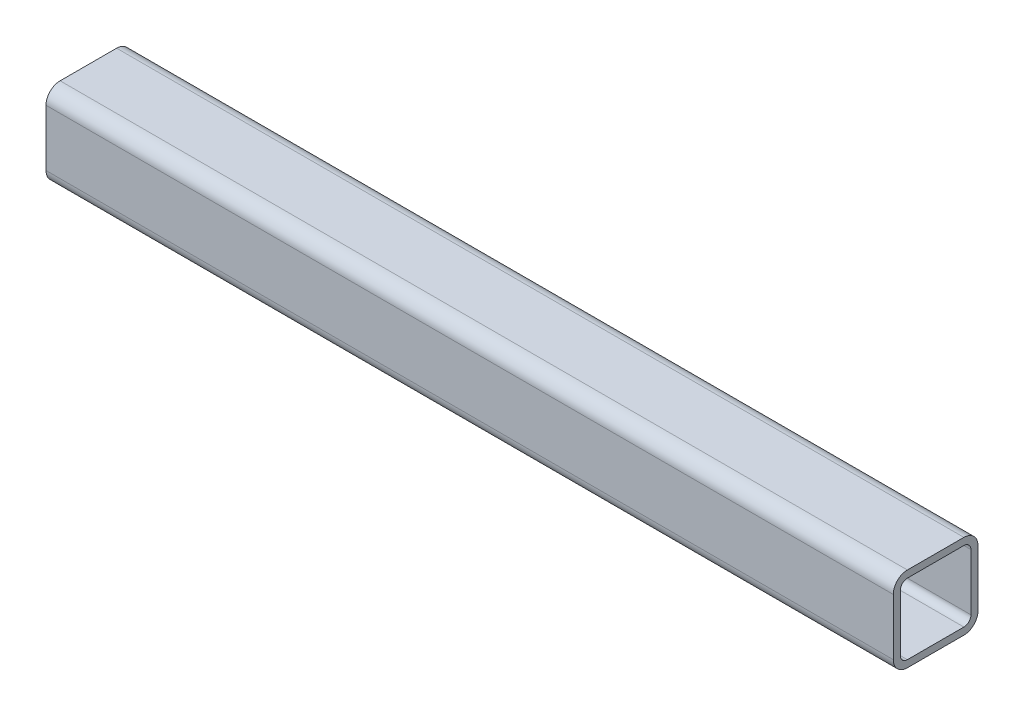
SolidWorks part; units mm, degrees
material "Plain Carbon Steel"
ref_plane "Front Plane" through (0, 0, 0) normal (0, 0, 1) x (1, 0, 0)
ref_plane "Top Plane" through (0, 0, 0) normal (0, 1, 0) x (1, 0, 0)
ref_plane "Right Plane" through (0, 0, 0) normal (1, 0, 0) x (0, 0, -1)
sketch3d "3DSketch1"
  line L0 (0, 0, 0) -> (-762, 0, 0)
  dimension "D1" = 762
other "Structural Member1"
ref_plane "Plane1" through (0, 0, 0) normal (-1, 0, 0) x (0, 0, 1)
sketch "Sketch1" plane through (0, 0, 0) normal (-1, 0, 0) x (0, 0, 1)
  line L0 (-25.4, -31.75) -> (25.4, -31.75)
  line L1 (-31.75, -25.4) -> (-31.75, 25.4)
  line L2 (25.4, 31.75) -> (-25.4, 31.75)
  line L3 (31.75, 25.4) -> (31.75, -25.4)
  line L4 (-25.4, -38.1) -> (25.4, -38.1)
  line L5 (-38.1, -25.4) -> (-38.1, 25.4)
  line L6 (25.4, 38.1) -> (-25.4, 38.1)
  line L7 (38.1, 25.4) -> (38.1, -25.4)
  line L8 (0, 0) -> (31.75, 0) construction
  line L9 (0, 0) -> (0, 31.75) construction
  arc A0 (38.1, 25.4) -> (25.4, 38.1) centre (25.4, 25.4) ccw
  arc A1 (25.4, -38.1) -> (38.1, -25.4) centre (25.4, -25.4) ccw
  arc A2 (-38.1, -25.4) -> (-25.4, -38.1) centre (-25.4, -25.4) ccw
  arc A3 (-25.4, 38.1) -> (-38.1, 25.4) centre (-25.4, 25.4) ccw
  arc A4 (-25.4, 31.75) -> (-31.75, 25.4) centre (-25.4, 25.4) ccw
  arc A5 (31.75, 25.4) -> (25.4, 31.75) centre (25.4, 25.4) ccw
  arc A6 (25.4, -31.75) -> (31.75, -25.4) centre (25.4, -25.4) ccw
  arc A7 (-31.75, -25.4) -> (-25.4, -31.75) centre (-25.4, -25.4) ccw
  point P3 (0, 38.1)
  point P4 (38.1, 0)
  point P5 (0, -38.1)
  point P6 (-38.1, 0)
  point P7 (-38.1, 38.1)
  point P8 (-38.1, -38.1)
  point P33 (0, 0)
  point P35 (38.1, -38.1)
  point P36 (38.1, 38.1)
  point P37 (0, 0)
  dimension "D1" = 12.7
  dimension "Thickness" = 6.35
  dimension "V_leg" = 76.2
